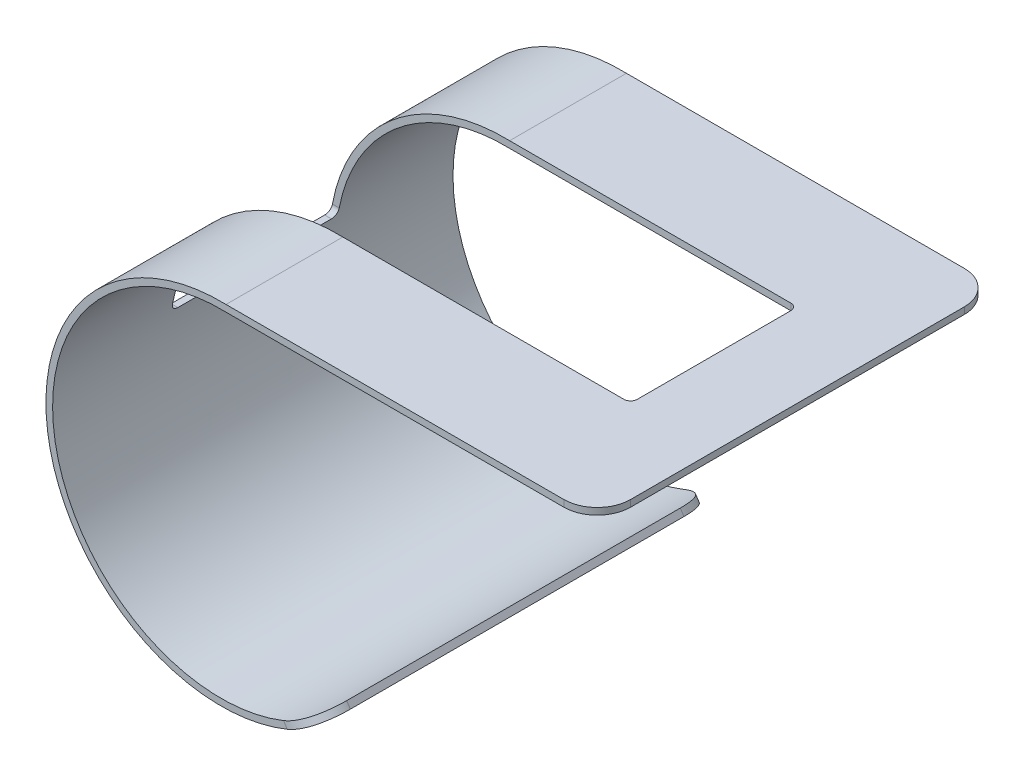
SolidWorks part; units mm, degrees
ref_plane "Front Plane" through (0, 0, 0) normal (0, 0, 1) x (1, 0, 0)
ref_plane "Top Plane" through (0, 0, 0) normal (0, 1, 0) x (1, 0, 0)
ref_plane "Right Plane" through (0, 0, 0) normal (1, 0, 0) x (0, 0, -1)
sketch "Sketch1" plane through (0, 0, 0) normal (0, 0, 1) x (1, 0, 0)
  line L0 (134.1685, 66.6489) -> (-7.119, 66.6489)
  arc A0 (-7.119, 66.6489) -> (27.4953, -55.8092) centre (-8.986, 0) ccw
  dimension "D1" = 66.675
  dimension "D2" = 141.2875
  dimension "D3" = 36.4813
extrude "Extrude-Thin1" add sketch "Sketch1" along normal mid plane 152.4 thin thin type one direction reverse wall 2.54
fillet "Fillet1" radius 12.7 4 edges at (26.8004, -54.7462, 76.2) (26.8004, -54.7462, -76.2) (134.1685, 65.3789, -76.2) (134.1685, 65.3789, 76.2)
sketch "Sketch2" plane through (0, 66.6489, 0) normal (0, 1, 0) x (1, 0, 0)
  line L0 (134.1685, -63.5) -> (134.1685, 63.5) construction
  line L1 (102.4185, 31.75) -> (-88.0815, 31.75)
  line L2 (102.4185, 31.75) -> (102.4185, -31.75)
  line L3 (102.4185, -31.75) -> (-88.0815, -31.75)
  line L4 (-88.0815, 31.75) -> (-88.0815, -31.75)
  dimension "D1" = 63.5
  dimension "D2" = 31.75
  dimension "D3" = 31.75
  dimension "D4" = 190.5
extrude "Cut-Extrude1" cut sketch "Sketch2" against normal mid plane 114.3
fillet "Fillet2" radius 2.54 4 edges at (-73.6973, 9.4989, -31.75) (-73.6973, 9.4989, 31.75) (102.4185, 65.3789, 31.75) (102.4185, 65.3789, -31.75)
